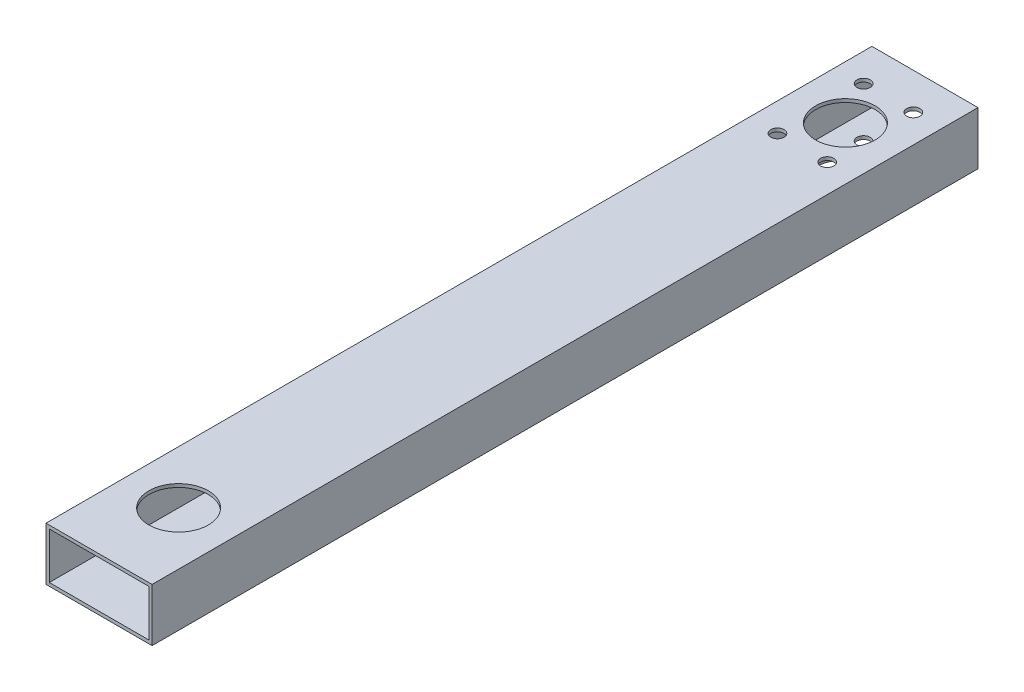
SolidWorks part; units mm, degrees
ref_plane "Front Plane" through (0, 0, 0) normal (0, 0, 1) x (1, 0, 0)
ref_plane "Top Plane" through (0, 0, 0) normal (0, 1, 0) x (1, 0, 0)
ref_plane "Right Plane" through (0, 0, 0) normal (1, 0, 0) x (0, 0, -1)
sketch "Sketch1" plane through (0, 0, 0) normal (0, 0, 1) x (1, 0, 0)
  line L0 (1.5875, 23.8125) -> (49.2125, 23.8125)
  line L1 (0, 0) -> (50.8, 0)
  line L2 (0, 0) -> (0, 25.4)
  line L3 (0, 25.4) -> (50.8, 25.4)
  line L4 (50.8, 0) -> (50.8, 25.4)
  line L5 (49.2125, 1.5875) -> (49.2125, 23.8125)
  line L6 (1.5875, 1.5875) -> (49.2125, 1.5875)
  line L7 (1.5875, 1.5875) -> (1.5875, 23.8125)
  dimension "D1" = 25.4
  dimension "D2" = 50.8
  dimension "D3" = 1.5875
extrude "Boss-Extrude1" add sketch "Sketch1" along normal blind 395.478
sketch "Sketch2" plane through (0, 25.4, 0) normal (0, 1, 0) x (1, 0, 0)
  line L0 (25.4, -38.1) -> (25.4, 0) construction
  line L1 (50.8, 0) -> (0, 0) construction
  line L2 (25.4, -395.478) -> (25.4, -357.378) construction
  line L3 (50.8, -395.478) -> (0, -395.478) construction
  line L4 (25.4, -38.1) -> (13.4937, -17.4778) construction
  line L5 (25.4, -38.1) -> (13.4938, -58.7222) construction
  circle A0 centre (25.4, -38.1) radius 14.224
  circle A1 centre (13.4937, -17.4778) radius 3.175
  circle A2 centre (13.4938, -58.7222) radius 3.175
  circle A3 centre (37.3062, -58.7222) radius 3.175
  circle A4 centre (37.3063, -17.4778) radius 3.175
  circle A5 centre (25.4, -357.378) radius 14.224
  dimension "D2" = 28.448
  dimension "D7" = 6.35
  dimension "D1" = 38.1
  dimension "D3" = 30
  dimension "D4" = 23.8125
  dimension "D5" = 30
  dimension "D6" = 23.8125
  dimension "D8" = 38.1
extrude "Cut-Extrude1" cut sketch "Sketch2" against normal through all both and the other way through all
